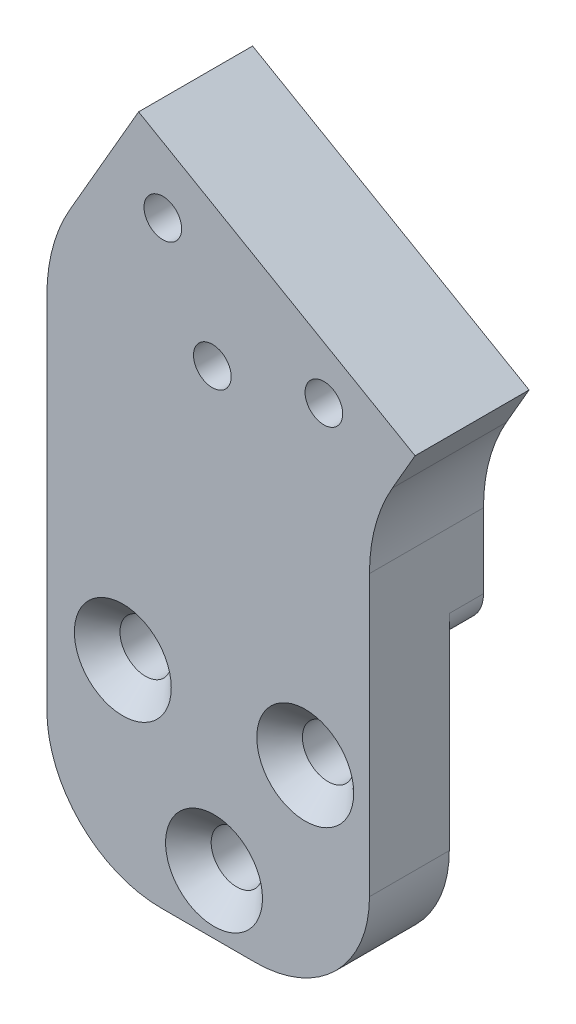
SolidWorks part; units mm, degrees
ref_plane "Front Plane" through (0, 0, 0) normal (0, 0, 1) x (1, 0, 0)
ref_plane "Top Plane" through (0, 0, 0) normal (0, 1, 0) x (1, 0, 0)
ref_plane "Right Plane" through (0, 0, 0) normal (1, 0, 0) x (0, 0, -1)
sketch "Sketch1" plane through (0, 0, 0) normal (0, 0, 1) x (1, 0, 0)
  line L5 (-14.6579, 119.617) -> (13.6331, 119.617)
  line L12 (13.6331, 119.617) -> (13.6331, 139.617)
  line L15 (-14.6579, 119.617) -> (-14.6579, 139.617)
  line L18 (-14.6579, 139.617) -> (-14.6579, 158.1769)
  line L20 (13.6331, 158.1769) -> (13.6331, 139.617)
  line L21 (-14.6579, 158.1769) -> (-14.6579, 165.1755)
  line L22 (-10.6157, 172.1769) -> (-14.6579, 165.1755)
  line L23 (-6.6157, 179.1051) -> (-10.6157, 172.1769)
  line L24 (17.6331, 165.1051) -> (13.6331, 158.1769)
  line L25 (-6.6157, 179.1051) -> (17.6331, 165.1051)
extrude "Boss-Extrude1" add sketch "Sketch1" along normal blind 9 and the other way blind 1
sketch "Sketch3" plane through (0, 0, -1) normal (0, 0, -1) x (-1, 0, 0)
  line L16 (-15, 144.2481) -> (-15, 114.7859)
  line L17 (-15, 114.7859) -> (15, 114.7859)
  line L18 (15, 114.7859) -> (15, 144.2481)
  arc A2 (15, 144.2481) -> (-15, 144.2481) centre (0, -5) ccw
extrude "Cut-Extrude1" cut sketch "Sketch3" against normal blind 3
sketch "Sketch7" plane through (0, 0, 9) normal (0, 0, -1) x (-1, 0, 0)
  line L2 (0, 124.7859) -> (0, 136.7859)
  line L3 (0, 136.7859) -> (8, 136.7859)
  line L4 (0, 136.7859) -> (-8, 136.7859)
  circle A0 centre (8, 136.7859) radius 2
  circle A1 centre (0, 124.7859) radius 2
  circle A2 centre (-8, 136.7859) radius 2
hole_wizard "CSK for M4 Countersunk Flat Head Screw2" positions "Sketch11" profile "Sketch10" countersink size "M4" standard "ISO" end condition through all
sketch "Sketch11" plane through (0, 0, 9) normal (0, 0, 1) x (1, 0, 0)
  point P0 (0, 0)
  point P1 (8, 136.7859)
  point P4 (-8, 136.7859)
  point P7 (0, 124.7859)
sketch "Sketch10" plane through (0, 0, 9) normal (1, 0, 0) x (0, -1, 0)
  line L0 (0, 0) -> (0, 10)
  line L1 (0, 10) -> (2.25, 10)
  line L2 (2.25, 10) -> (2.25, 2)
  line L3 (2.25, 2) -> (4.25, 0)
  line L5 (4.25, 0) -> (0, 0)
  line L6 (-2.25, 2) -> (-4.25, 0) construction
  line L11 (0, -6.35) -> (0, 107.95) construction
  dimension "Thru Hole Dia." = 4.5
  dimension "Thru Hole Depth" = 10
  dimension "Near C'Sink Dia." = 8.5
  dimension "Near C'Sink Angle" = 90
fillet "Fillet1" radius 15 2 edges at (13.6331, 158.1769, 4) (-14.6579, 165.1755, 4)
fillet "Fillet2" radius 10 2 edges at (-14.6579, 119.617, 5.5) (13.6331, 119.617, 5.5)
fillet "Fillet3" radius 3 2 edges at (13.6331, 144.3792, 0.5) (-14.6579, 144.2821, 0.5)
sketch "Sketch12" plane through (0, 0, -1) normal (0, 0, -1) x (-1, 0, 0)
  circle A0 centre (4.4913, 172.1051) radius 1.65
  circle A1 centre (-9.6331, 165.1051) radius 1.65
  circle A2 centre (0.1468, 163.0385) radius 1.65
extrude "Cut-Extrude2" cut sketch "Sketch12" against normal through all
